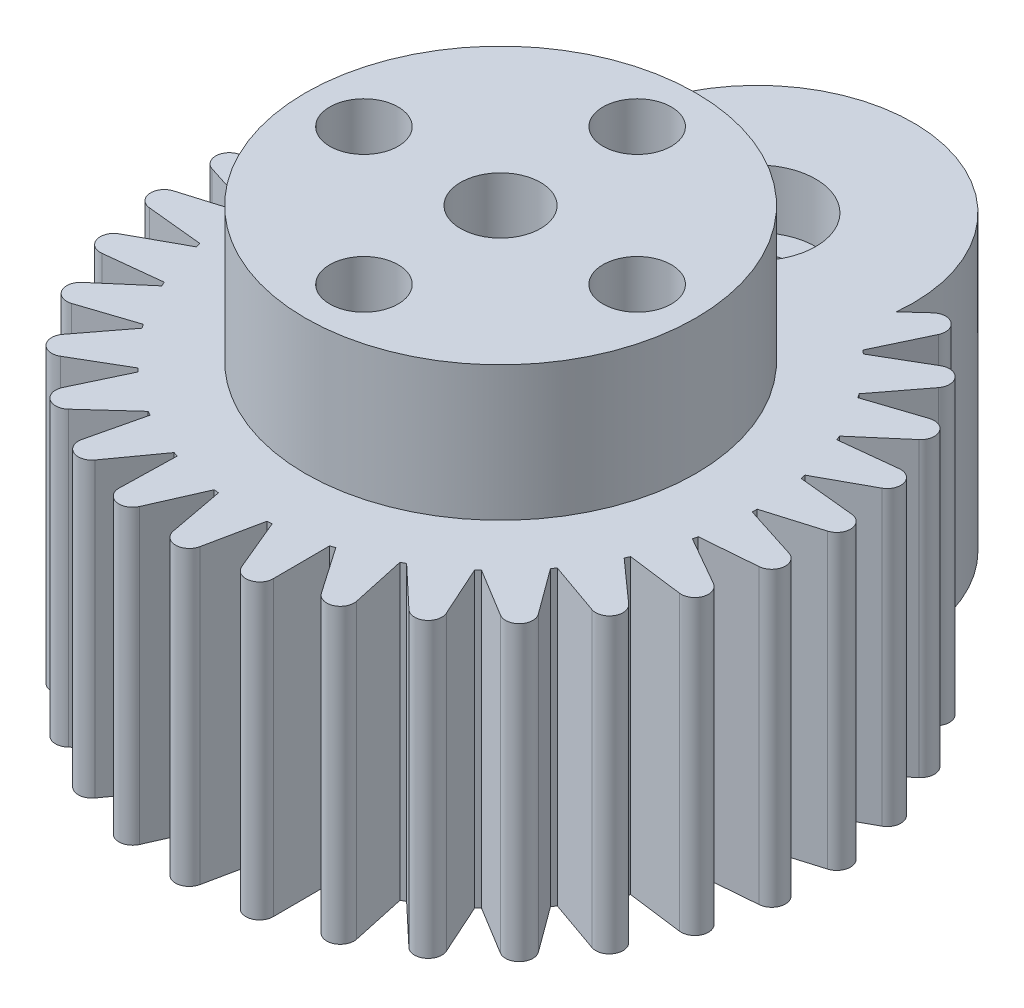
SolidWorks part; units mm, degrees
ref_plane "前视基准面" through (0, 0, 0) normal (0, 0, 1) x (1, 0, 0)
ref_plane "上视基准面" through (0, 0, 0) normal (0, 1, 0) x (1, 0, 0)
ref_plane "右视基准面" through (0, 0, 0) normal (1, 0, 0) x (0, 0, -1)
other "Configuration Table"
sketch "草图1" plane through (0, 0, 0) normal (0, 1, 0) x (1, 0, 0)
  line L0 (0, 0) -> (13.15, 0) construction
  line L1 (13.15, 0) -> (15.9283, 0.8312)
  line L2 (14.3952, 1.3746) -> (0, 0) construction
  line L3 (12.9124, 2.4887) -> (15.7978, 2.1983)
  line L5 (12.8626, -2.734) -> (15.7531, -2.4987)
  line L7 (13.1476, -0.2503) -> (15.9096, -1.1343)
  line L8 (12.0131, -5.3486) -> (14.8893, -5.7193)
  line L10 (12.8083, -2.9784) -> (15.3261, -4.4173)
  line L11 (10.6386, -7.7294) -> (13.3749, -8.69)
  line L13 (11.9091, -5.5763) -> (14.0728, -7.5072)
  line L14 (8.7991, -9.7724) -> (11.2758, -11.2809)
  line L16 (10.4895, -7.9305) -> (12.2044, -10.2691)
  line L17 (6.575, -11.3882) -> (8.684, -13.3787)
  line L19 (8.6114, -9.9381) -> (9.8027, -12.5821)
  line L20 (4.0636, -12.5064) -> (5.7126, -14.8919)
  line L22 (6.357, -11.5113) -> (6.9725, -14.3453)
  line L23 (1.3745, -13.078) -> (2.4916, -15.7542)
  line L25 (3.8248, -12.5815) -> (3.8376, -15.4815)
  line L26 (-1.3745, -13.078) -> (-0.8383, -15.928)
  line L28 (1.1253, -13.1018) -> (0.535, -15.941)
  line L29 (-4.0636, -12.5064) -> (-4.1316, -15.4056)
  line L31 (-1.6233, -13.0494) -> (-2.7911, -15.7039)
  line L32 (-6.575, -11.3882) -> (-7.2443, -14.2099)
  line L34 (-4.3009, -12.4268) -> (-5.9951, -14.7804)
  line L35 (-8.7991, -9.7724) -> (-10.0404, -12.3932)
  line L37 (-6.7906, -11.261) -> (-8.9371, -13.211)
  line L38 (-10.6386, -7.7294) -> (-12.3977, -10.0349)
  line L40 (-8.9835, -9.6031) -> (-11.4885, -11.0642)
  line L41 (-12.0131, -5.3486) -> (-14.2132, -7.238)
  line L43 (-10.7838, -7.5255) -> (-13.5379, -8.4338)
  line L44 (-12.8626, -2.734) -> (-15.4074, -4.1247)
  line L46 (-12.1128, -5.1189) -> (-14.9955, -5.4348)
  line L47 (-13.15, 0) -> (-15.9283, -0.8312)
  line L49 (-12.9124, -2.4887) -> (-15.7978, -2.1983)
  line L50 (-12.8626, 2.734) -> (-15.7531, 2.4987)
  line L52 (-13.1476, 0.2503) -> (-15.9096, 1.1343)
  line L53 (-12.0131, 5.3486) -> (-14.8893, 5.7193)
  line L55 (-12.8083, 2.9784) -> (-15.3261, 4.4173)
  line L56 (-10.6386, 7.7294) -> (-13.3749, 8.69)
  line L58 (-11.9091, 5.5763) -> (-14.0728, 7.5072)
  line L59 (-8.7991, 9.7724) -> (-11.2758, 11.2809)
  line L61 (-10.4895, 7.9305) -> (-12.2044, 10.2691)
  line L62 (-6.575, 11.3882) -> (-8.684, 13.3787)
  line L64 (-8.6114, 9.9381) -> (-9.8027, 12.5821)
  line L65 (-4.0636, 12.5064) -> (-5.7126, 14.8919)
  line L67 (-6.357, 11.5113) -> (-6.9725, 14.3453)
  line L68 (-1.3745, 13.078) -> (-2.4916, 15.7542)
  line L70 (-3.8248, 12.5815) -> (-3.8376, 15.4815)
  line L71 (1.3745, 13.078) -> (0.8383, 15.928)
  line L73 (-1.1253, 13.1018) -> (-0.535, 15.941)
  line L74 (4.0636, 12.5064) -> (4.1316, 15.4056)
  line L76 (1.6233, 13.0494) -> (2.7911, 15.7039)
  line L77 (6.575, 11.3882) -> (7.2443, 14.2099)
  line L79 (4.3009, 12.4268) -> (5.9951, 14.7804)
  line L80 (8.7991, 9.7724) -> (10.0404, 12.3932)
  line L82 (6.7906, 11.261) -> (8.9371, 13.211)
  line L83 (10.6386, 7.7294) -> (12.3977, 10.0349)
  line L85 (8.9835, 9.6031) -> (11.4885, 11.0642)
  line L86 (12.0131, 5.3486) -> (14.2132, 7.238)
  line L88 (10.7838, 7.5255) -> (13.5379, 8.4338)
  line L89 (12.8626, 2.734) -> (15.4074, 4.1247)
  line L91 (12.1128, 5.1189) -> (14.9955, 5.4348)
  arc A0 (6.7906, 11.261) -> (6.575, 11.3882) centre (0, 0) ccw
  arc A1 (15.7978, 2.1983) -> (15.9283, 0.8312) centre (15.7277, 1.5018) cw
  arc A2 (15.9096, -1.1343) -> (15.7531, -2.4987) centre (15.6963, -1.801) cw
  arc A3 (15.3261, -4.4173) -> (14.8893, -5.7193) centre (14.9788, -5.025) cw
  arc A4 (14.0728, -7.5072) -> (13.3749, -8.69) centre (13.6067, -8.0295) cw
  arc A5 (12.2044, -10.2691) -> (11.2758, -11.2809) centre (11.64, -10.683) cw
  arc A6 (9.8027, -12.5821) -> (8.684, -13.3787) centre (9.1645, -12.8697) cw
  arc A7 (6.9725, -14.3453) -> (5.7126, -14.8919) centre (6.2884, -14.4938) cw
  arc A8 (3.8376, -15.4815) -> (2.4916, -15.7542) centre (3.1376, -15.4846) cw
  arc A9 (0.535, -15.941) -> (-0.8383, -15.928) centre (-0.1504, -15.7985) cw
  arc A10 (-2.7911, -15.7039) -> (-4.1316, -15.4056) centre (-3.4318, -15.422) cw
  arc A11 (-5.9951, -14.7804) -> (-7.2443, -14.2099) centre (-6.5632, -14.3715) cw
  arc A12 (-8.9371, -13.211) -> (-10.0404, -12.3932) centre (-9.4078, -12.6929) cw
  arc A13 (-11.4885, -11.0642) -> (-12.3977, -10.0349) centre (-11.8412, -10.4595) cw
  arc A14 (-13.5379, -8.4338) -> (-14.2132, -7.238) centre (-13.7571, -7.769) cw
  arc A15 (-14.9955, -5.4348) -> (-15.4074, -4.1247) centre (-15.0718, -4.739) cw
  arc A16 (-15.7978, -2.1983) -> (-15.9283, -0.8312) centre (-15.7277, -1.5018) cw
  arc A17 (-15.9096, 1.1343) -> (-15.7531, 2.4987) centre (-15.6963, 1.801) cw
  arc A18 (-15.3261, 4.4173) -> (-14.8893, 5.7193) centre (-14.9788, 5.025) cw
  arc A19 (-14.0728, 7.5072) -> (-13.3749, 8.69) centre (-13.6067, 8.0295) cw
  arc A20 (-12.2044, 10.2691) -> (-11.2758, 11.2809) centre (-11.64, 10.683) cw
  arc A21 (-9.8027, 12.5821) -> (-8.684, 13.3787) centre (-9.1645, 12.8697) cw
  arc A22 (-6.9725, 14.3453) -> (-5.7126, 14.8919) centre (-6.2884, 14.4938) cw
  arc A23 (-3.8376, 15.4815) -> (-2.4916, 15.7542) centre (-3.1376, 15.4846) cw
  arc A24 (-0.535, 15.941) -> (0.8383, 15.928) centre (0.1504, 15.7985) cw
  arc A25 (2.7911, 15.7039) -> (4.1316, 15.4056) centre (3.4318, 15.422) cw
  arc A26 (5.9951, 14.7804) -> (7.2443, 14.2099) centre (6.5632, 14.3715) cw
  arc A27 (8.9371, 13.211) -> (10.0404, 12.3932) centre (9.4078, 12.6929) cw
  arc A28 (11.4885, 11.0642) -> (12.3977, 10.0349) centre (11.8412, 10.4595) cw
  arc A29 (13.5379, 8.4338) -> (14.2132, 7.238) centre (13.7571, 7.769) cw
  arc A30 (14.9955, 5.4348) -> (15.4074, 4.1247) centre (15.0718, 4.739) cw
  arc A31 (4.3009, 12.4268) -> (4.0636, 12.5064) centre (0, 0) ccw
  arc A32 (8.9835, 9.6031) -> (8.7991, 9.7724) centre (0, 0) ccw
  arc A33 (10.7838, 7.5255) -> (10.6386, 7.7294) centre (0, 0) ccw
  arc A34 (12.1128, 5.1189) -> (12.0131, 5.3486) centre (0, 0) ccw
  arc A35 (1.6233, 13.0494) -> (1.3745, 13.078) centre (0, 0) ccw
  arc A36 (-1.1253, 13.1018) -> (-1.3745, 13.078) centre (0, 0) ccw
  arc A37 (-3.8248, 12.5815) -> (-4.0636, 12.5064) centre (0, 0) ccw
  arc A38 (-6.357, 11.5113) -> (-6.575, 11.3882) centre (0, 0) ccw
  arc A39 (-8.6114, 9.9381) -> (-8.7991, 9.7724) centre (0, 0) ccw
  arc A40 (-10.4895, 7.9305) -> (-10.6386, 7.7294) centre (0, 0) ccw
  arc A41 (-11.9091, 5.5763) -> (-12.0131, 5.3486) centre (0, 0) ccw
  arc A42 (-12.8083, 2.9784) -> (-12.8626, 2.734) centre (0, 0) ccw
  arc A43 (-13.1476, 0.2503) -> (-13.15, 0) centre (0, 0) ccw
  arc A44 (-12.9124, -2.4887) -> (-12.8626, -2.734) centre (0, 0) ccw
  arc A45 (-12.1128, -5.1189) -> (-12.0131, -5.3486) centre (0, 0) ccw
  arc A46 (-10.7838, -7.5255) -> (-10.6386, -7.7294) centre (0, 0) ccw
  arc A47 (-8.9835, -9.6031) -> (-8.7991, -9.7724) centre (0, 0) ccw
  arc A48 (-6.7906, -11.261) -> (-6.575, -11.3882) centre (0, 0) ccw
  arc A49 (-4.3009, -12.4268) -> (-4.0636, -12.5064) centre (0, 0) ccw
  arc A50 (-1.6233, -13.0494) -> (-1.3745, -13.078) centre (0, 0) ccw
  arc A51 (1.1253, -13.1018) -> (1.3745, -13.078) centre (0, 0) ccw
  arc A52 (3.8248, -12.5815) -> (4.0636, -12.5064) centre (0, 0) ccw
  arc A53 (6.357, -11.5113) -> (6.575, -11.3882) centre (0, 0) ccw
  arc A54 (8.6114, -9.9381) -> (8.7991, -9.7724) centre (0, 0) ccw
  arc A55 (10.4895, -7.9305) -> (10.6386, -7.7294) centre (0, 0) ccw
  arc A56 (11.9091, -5.5763) -> (12.0131, -5.3486) centre (0, 0) ccw
  arc A57 (12.8083, -2.9784) -> (12.8626, -2.734) centre (0, 0) ccw
  arc A58 (13.1476, -0.2503) -> (13.15, 0) centre (0, 0) ccw
  arc A59 (12.9124, 2.4887) -> (12.8626, 2.734) centre (0, 0) ccw
  circle A60 centre (0, 0) radius 2.05
  circle A61 centre (0, 0) radius 7 construction
  circle A62 centre (0, 7) radius 1.75
  circle A63 centre (7, 0) radius 1.75
  circle A64 centre (0, -7) radius 1.75
  circle A65 centre (-7, 0) radius 1.75
  point P157 (0, 0)
  point P225 (0, 0)
  dimension "D1" = 26.3
  dimension "D2" = 2.9
  dimension "D4" = 0.7
  dimension "D6" = 4.1
  dimension "D7" = 14
  dimension "D8" = 3.5
  dimension "D3" = 2.5
  dimension "D5" = 30
  dimension "D9" = 4
extrude "凸台-拉伸1" add sketch "草图1" along normal blind 15
sketch "草图2" plane through (0, 15, 0) normal (0, 1, 0) x (1, 0, 0)
  circle A0 centre (0, 0) radius 10
  circle A1 centre (0, -7) radius 1.75 construction
  circle A2 centre (7, 0) radius 1.75 construction
  circle A3 centre (0, 7) radius 1.75 construction
  circle A4 centre (0, 0) radius 2.05 construction
  circle A5 centre (-7, 0) radius 1.75 construction
  circle A6 centre (0, -7) radius 1.75
  circle A7 centre (7, 0) radius 1.75
  circle A8 centre (0, 7) radius 1.75
  circle A9 centre (0, 0) radius 2.05
  circle A10 centre (-7, 0) radius 1.75
  dimension "D1" = 20
extrude "凸台-拉伸2" add sketch "草图2" along normal blind 6.9
sketch "草图3" plane through (0, 0, 0) normal (0, -1, 0) x (1, 0, 0)
  line L0 (0, 0) -> (0, -13.15) construction
  line L1 (-6.9714, -11.15) -> (6.9714, -11.15) construction
  line L2 (0, -21.15) -> (-8, -21.15) construction
  circle A0 centre (0, -13.15) radius 8
  circle A1 centre (0, 0) radius 13.15 construction
  circle A3 centre (0, -7) radius 1.75
  point P7 (0, -11.15)
  dimension "D1" = 16
  dimension "D2" = 10
extrude "凸台-拉伸3" add sketch "草图3" against normal blind 15
sketch "草图4" plane through (0, 0, 0) normal (0, -1, 0) x (1, 0, 0)
  line L0 (-3, -16.5041) -> (3, -16.5041) construction
  line L1 (-3, -16.5041) -> (-3, -20.5662)
  line L2 (3, -16.5041) -> (3, -20.5662)
  arc A1 (3, -16.5041) -> (-3, -16.5041) centre (0, -13.15) ccw
  arc A2 (-7.9886, -12.7224) -> (7.9569, -12.3205) centre (0, -13.15) ccw construction
  arc A3 (-3, -20.5662) -> (3, -20.5662) centre (0, -13.15) ccw
  point P6 (0, -16.5041)
  dimension "D1" = 9
  dimension "D2" = 6
extrude "切除-拉伸1" cut sketch "草图4" against normal blind 7.5
sketch "草图5" plane through (0, 7.5, 0) normal (0, -1, 0) x (1, 0, 0)
  circle A0 centre (0, -13.15) radius 1.65
  dimension "D1" = 3.3
extrude "切除-拉伸2" cut sketch "草图5" against normal blind 7.5
sketch "草图6" plane through (0, 15, 0) normal (0, 1, 0) x (1, 0, 0)
  circle A0 centre (0, 13.15) radius 3
  dimension "D1" = 6
extrude "切除-拉伸3" cut sketch "草图6" against normal blind 3
